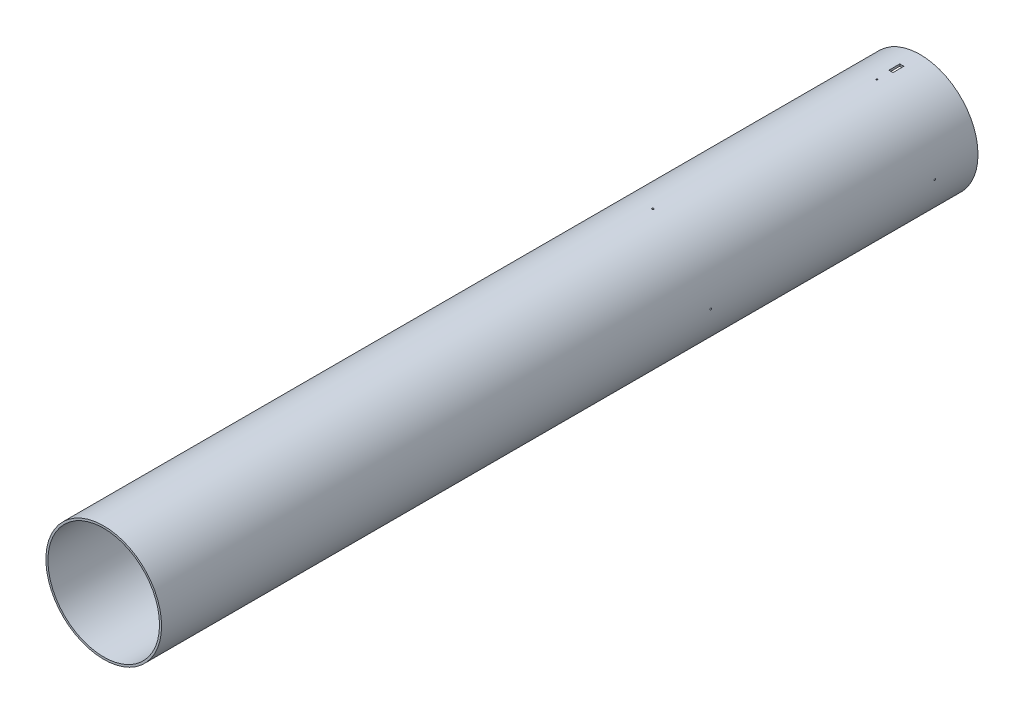
SolidWorks part; units mm, degrees
ref_plane "Front Plane" through (0, 0, 0) normal (0, 0, 1) x (1, 0, 0)
ref_plane "Top Plane" through (0, 0, 0) normal (0, 1, 0) x (1, 0, 0)
ref_plane "Right Plane" through (0, 0, 0) normal (1, 0, 0) x (0, 0, -1)
sketch "Sketch1" plane through (0, 0, 0) normal (0, 0, 1) x (1, 0, 0)
  circle A0 centre (0, 0) radius 82
  circle A1 centre (0, 0) radius 85
  dimension "D1" = 164
  dimension "D2" = 170
extrude "Boss-Extrude1" add sketch "Sketch1" along normal blind 1200
sketch "Sketch2" plane through (0, 0, 0) normal (0, 1, 0) x (1, 0, 0)
  line L0 (85, 0) -> (-85, 0) construction
  circle A0 centre (0, -393) radius 1.25
  dimension "D2" = 2.5
  dimension "D1" = 393
extrude "Cut-Extrude1" cut sketch "Sketch2" against normal blind 900
pattern_circular "CirPattern1" count 4 over 360 about axis through (0, 0, 0) along (0, 0, 1) of "Cut-Extrude1"
sketch "Sketch3" plane through (0, 0, 0) normal (0, 1, 0) x (1, 0, 0)
  line L0 (85, 0) -> (-85, 0) construction
  line L1 (-3, -27) -> (3, -27)
  line L2 (-3, -27) -> (-3, -33)
  line L3 (-3, -33) -> (3, -33)
  line L4 (3, -27) -> (3, -33)
  line L5 (-3, -27) -> (3, -33) construction
  line L6 (-3, -33) -> (3, -27) construction
  line L8 (-3, -33) -> (3, -33)
  line L9 (-3, -33) -> (-3, -43)
  line L10 (-3, -43) -> (3, -43)
  line L11 (3, -33) -> (3, -43)
  point P0 (0, -30)
  dimension "D1" = 30
  dimension "D2" = 6
  dimension "D3" = 6
  dimension "D4" = 10
extrude "Cut-Extrude2" cut sketch "Sketch3" against normal blind 104 contours L4 L1 L2 L3 | L11 L3 L9 L10
pattern_circular "CirPattern2" count 2 every 180 about axis through (0, 0, 0) along (0, 0, 1) of "Cut-Extrude2"
sketch "Sketch5" plane through (0, 0, 0) normal (0, 1, 0) x (1, 0, 0)
  line L0 (82, 0) -> (-82, 0) construction
  circle A0 centre (0, -63.5) radius 1
  dimension "D2" = 2
  dimension "D1" = 63.5
extrude "Cut-Extrude3" cut sketch "Sketch5" against normal blind 104
pattern_circular "CirPattern3" count 4 every 90 about axis through (0, 0, 0) along (0, 0, 1) of "Cut-Extrude3"
sketch "Sketch6" plane through (0, 0, 0) normal (1, 0, 0) x (0, 0, -1)
  line L0 (-62.5, 0) -> (-64.5, 0) construction
  circle A0 centre (-63.5, 0) radius 1
